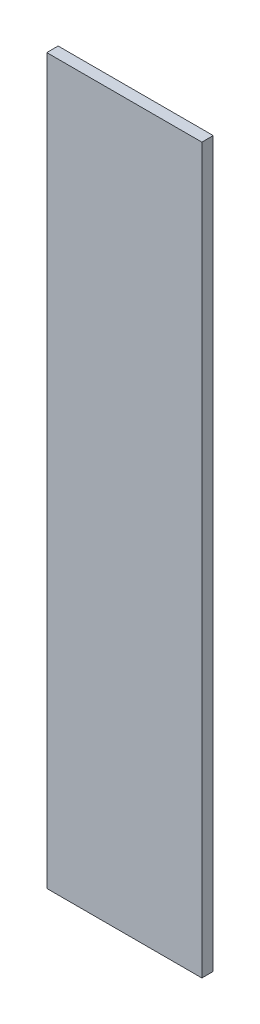
SolidWorks part; units mm, degrees
ref_plane "Alzado" through (0, 0, 0) normal (0, 0, 1) x (1, 0, 0)
ref_plane "Planta" through (0, 0, 0) normal (0, 1, 0) x (1, 0, 0)
ref_plane "Vista lateral" through (0, 0, 0) normal (1, 0, 0) x (0, 0, -1)
sketch "Croquis1" plane through (0, 0, 0) normal (0, 0, 1) x (1, 0, 0)
  line L1 (-66.3295, 77.6274) -> (8.6705, 77.6274)
  line L2 (-66.3295, 77.6274) -> (-66.3295, -272.3726)
  line L3 (-66.3295, -272.3726) -> (8.6705, -272.3726)
  line L4 (8.6705, 77.6274) -> (8.6705, -272.3726)
  dimension "D1" = 75
  dimension "D2" = 350
extrude "Saliente-Extruir1" add sketch "Croquis1" along normal blind 5.5
